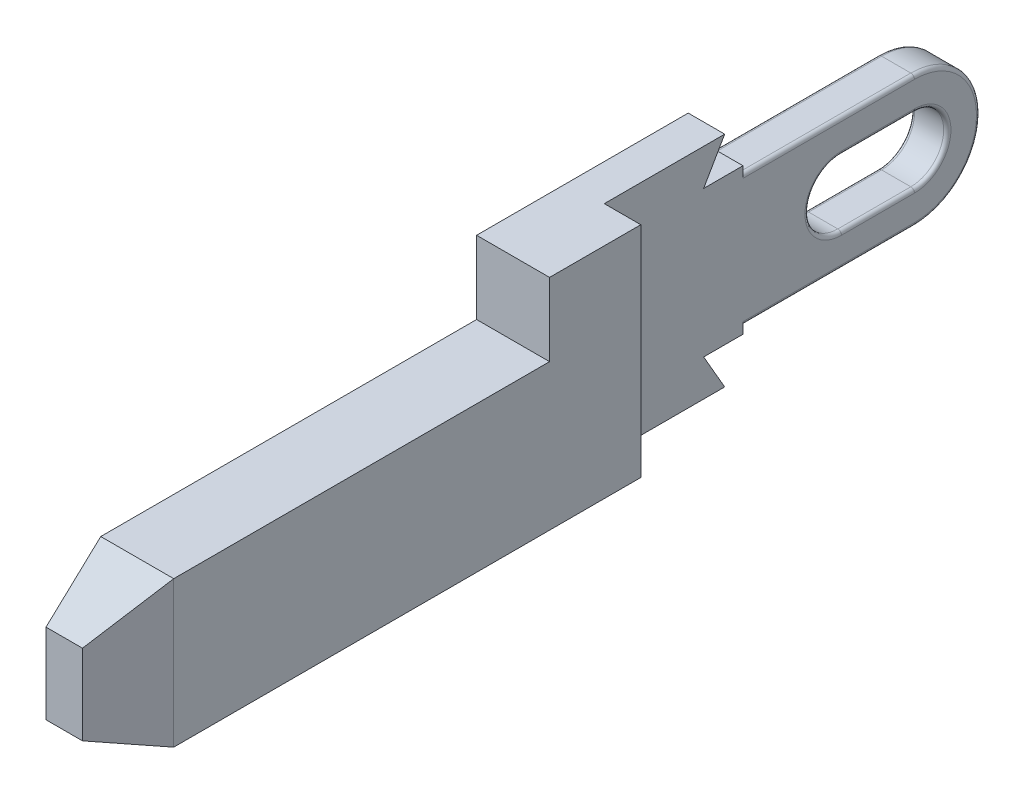
SolidWorks part; units mm, degrees
ref_plane "Спереди" through (0, 0, 0) normal (0, 0, 1) x (1, 0, 0)
ref_plane "Сверху" through (0, 0, 0) normal (0, 1, 0) x (1, 0, 0)
ref_plane "Справа" through (0, 0, 0) normal (1, 0, 0) x (0, 0, -1)
sketch "Эскиз1" plane through (0, 0, 0) normal (1, 0, 0) x (0, 0, -1)
  line L0 (0, 0) -> (14.6296, 0) construction
  line L1 (0, 0) -> (0, 1.1)
  line L2 (0, 1.1) -> (2, 2)
  line L3 (2, 2) -> (12.3, 2)
  line L4 (12.3, 2) -> (12.3, 4)
  line L5 (12.3, 4) -> (18.1, 4)
  line L6 (23.3, 1) -> (21.3, 1) construction
  line L7 (21.3, 1.9) -> (23.3, 1.9)
  line L8 (18.1, 4) -> (17.5226, 3)
  line L9 (18.6, 2.8) -> (23.3, 2.8)
  line L10 (0, 0) -> (0, -1.1)
  line L11 (0, -1.1) -> (2, -2)
  line L12 (2, -2) -> (18.1, -2)
  line L13 (21.3, 0.1) -> (23.3, 0.1)
  line L14 (17.5226, 3) -> (18.6, 3)
  line L15 (18.1, -2) -> (17.5226, -1)
  line L16 (18.6, -0.8) -> (23.3, -0.8)
  line L17 (18.6, 3) -> (18.6, 2.8)
  line L18 (17.5226, -1) -> (18.6, -1)
  line L19 (18.6, -1) -> (18.6, -0.8)
  arc A0 (23.3, 2.8) -> (23.3, -0.8) centre (23.3, 1) cw
  arc A1 (23.3, 0.1) -> (23.3, 1.9) centre (23.3, 1) ccw
  arc A2 (21.3, 1.9) -> (21.3, 0.1) centre (21.3, 1) ccw
  point P9 (25.1, 1)
  dimension "D15" = 1.8
  dimension "D16" = 7
  dimension "D17" = 1.8
  dimension "D18" = 1.8
  dimension "D19" = 2
  dimension "D1" = 4
  dimension "D2" = 2
  dimension "D3" = 2
  dimension "D4" = 2
  dimension "D5" = 2.2
  dimension "D6" = 1.1
  dimension "D7" = 12.3
  dimension "D8" = 6
  dimension "D9" = 5.8
  dimension "D10" = 3.6
  dimension "D11" = 60
  dimension "D12" = 1.2
  dimension "D13" = 5.8
  dimension "D14" = 60
  dimension "D20" = 1.8
  dimension "D21" = 0.5
  dimension "D22" = 0.5
  dimension "D23" = 4
  dimension "D24" = 0.2
extrude "Бобышка-Вытянуть1" add sketch "Эскиз1" along normal blind 2
sketch "Эскиз2" plane through (2, 0, 0) normal (1, 0, 0) x (0, 0, -1)
  line L0 (12.3, 4) -> (12.3, 2) construction
  line L1 (14.8, 5.6301) -> (26.841, 5.6301)
  line L2 (14.8, 5.6301) -> (14.8, -3.3416)
  line L3 (14.8, -3.3416) -> (26.841, -3.3416)
  line L4 (26.841, 5.6301) -> (26.841, -3.3416)
  dimension "D1" = 2.5
extrude "Вырез-Вытянуть1" cut sketch "Эскиз2" against normal blind 1
chamfer "Фаска1" distance 0.5 distance2 2 1 edges at (2, 0, 0)
chamfer "Фаска2" distance 2 distance2 0.5 1 edges at (0, 0, 0)
fillet "Скругление1" radius 0.1 14 edges at (1, -0.8, -20.95) (1, 1, -25.1) (1, 2.8, -20.95) (0, -0.8, -20.95) (0, 1, -25.1) (0, 2.8, -20.95) (1, 1, -20.4) (1, 1.9, -22.3) (1, 1, -24.2) (1, 0.1, -22.3) (0, 1, -20.4) (0, 1.9, -22.3) (0, 1, -24.2) (0, 0.1, -22.3)
